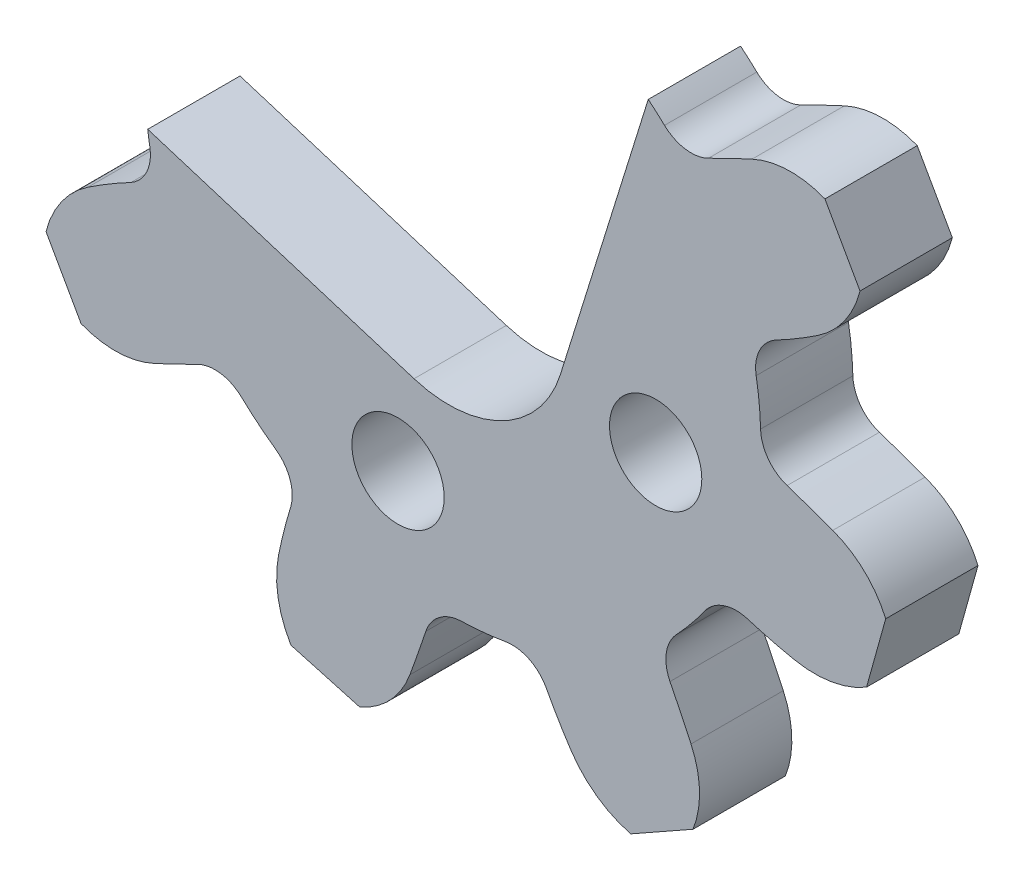
SolidWorks part; units mm, degrees
ref_plane "Front Plane" through (0, 0, 0) normal (0, 0, 1) x (1, 0, 0)
ref_plane "Top Plane" through (0, 0, 0) normal (0, 1, 0) x (1, 0, 0)
ref_plane "Right Plane" through (0, 0, 0) normal (1, 0, 0) x (0, 0, -1)
sketch "Sketch2" plane through (0, 0, 0) normal (0, 0, 1) x (1, 0, 0)
  line L0 (-5.1308, -13.1284) -> (-2.8946, -13.7516)
  line L5 (5.9154, -12.9172) -> (7.9373, -11.7766)
  line L6 (13.577, -4.957) -> (14.2002, -2.7208)
  line L7 (13.3658, 6.0892) -> (12.2252, 8.1111)
  line L8 (0.1374, 0.3112) -> (-9.7848, 0.3112) construction
  line L9 (0.1374, 0.3112) -> (0.1374, 8.1111) construction
  line L19 (6.4827, 8.0402) -> (3.6283, -1.1294)
  line L20 (-1.1294, -3.6283) -> (-9.7848, -0.9339)
  line L21 (-13.0911, -5.4669) -> (-11.9505, -7.4888)
  arc A0 (-5.1322, -9.223) -> (-5.5313, -10.7891) centre (10.0419, -13.9237) ccw
  arc A1 (-5.5313, -10.7891) -> (-5.1308, -13.1284) centre (-2.299, -11.4397) ccw
  arc A2 (-2.8946, -13.7516) -> (-1.2658, -12.0309) centre (-4.0784, -10.9998) ccw
  arc A3 (-1.2658, -12.0309) -> (-0.7472, -10.5464) centre (-49.4495, 5.6342) ccw
  arc A4 (0.4126, -9.685) -> (-0.7472, -10.5464) centre (0.4472, -10.9432) ccw
  arc A5 (-5.1322, -9.223) -> (-5.6219, -7.8638) centre (-6.3468, -8.8928) ccw
  arc A6 (3.1529, -10.1566) -> (3.9781, -11.5463) centre (17.2065, -2.7508) ccw
  arc A7 (3.9781, -11.5463) -> (5.9154, -12.9172) centre (6.7237, -9.7207) ccw
  arc A8 (7.9373, -11.7766) -> (7.8724, -9.4082) centre (5.1544, -10.6679) ccw
  arc A9 (7.8724, -9.4082) -> (7.1893, -7.9918) centre (-38.6897, -30.9881) ccw
  arc A10 (7.4004, -6.5626) -> (7.1893, -7.9918) centre (8.3145, -7.4278) ccw
  arc A11 (3.1529, -10.1566) -> (1.8456, -9.5418) centre (2.0606, -10.782) ccw
  arc A12 (9.6715, -4.9584) -> (11.2376, -5.3575) centre (14.3723, 10.2157) ccw
  arc A13 (11.2376, -5.3575) -> (13.577, -4.957) centre (11.8882, -2.1252) ccw
  arc A14 (14.2002, -2.7208) -> (12.4795, -1.092) centre (11.4483, -3.9046) ccw
  arc A15 (12.4795, -1.092) -> (10.9949, -0.5734) centre (-5.1856, -49.2757) ccw
  arc A16 (10.1336, 0.5864) -> (10.9949, -0.5734) centre (11.3917, 0.621) ccw
  arc A17 (9.6715, -4.9584) -> (8.3124, -5.4481) centre (9.3413, -6.173) ccw
  arc A18 (10.6052, 3.3267) -> (11.9948, 4.1519) centre (3.1994, 17.3804) ccw
  arc A19 (11.9948, 4.1519) -> (13.3658, 6.0892) centre (10.1693, 6.8975) ccw
  arc A20 (12.2252, 8.1111) -> (9.8568, 8.0462) centre (11.1165, 5.3282) ccw
  arc A21 (9.8568, 8.0462) -> (8.4403, 7.3631) centre (31.4367, -38.5159) ccw
  arc A22 (7.0112, 7.5742) -> (8.4403, 7.3631) centre (7.8763, 8.4883) ccw
  arc A23 (10.6052, 3.3267) -> (9.9904, 2.0194) centre (11.2305, 2.2344) ccw
  arc A25 (7.0112, 7.5742) -> (6.4827, 8.0402) centre (0.1374, 0.3112) ccw
  arc A26 (10.1336, 0.5864) -> (9.9904, 2.0194) centre (0.1374, 0.3112) ccw
  arc A27 (7.4004, -6.5626) -> (8.3124, -5.4481) centre (0.1374, 0.3112) ccw
  arc A28 (0.4126, -9.685) -> (1.8456, -9.5418) centre (0.1374, 0.3112) ccw
  arc A29 (-6.7364, -6.9518) -> (-5.6219, -7.8638) centre (0.1374, 0.3112) ccw
  circle A32 centre (-1.6501, -6.4856) radius 1.5
  circle A34 centre (6.7237, -1.7764) radius 1.5
  arc A83 (-1.1294, -3.6283) -> (3.6283, -1.1294) centre (0, 0) ccw
  arc A84 (-9.7848, -0.9339) -> (-9.7156, -1.397) centre (0.1374, 0.3112) ccw
  arc A85 (-10.3305, -2.7043) -> (-9.7156, -1.397) centre (-10.9558, -1.612) ccw
  arc A86 (-10.3305, -2.7043) -> (-11.7201, -3.5295) centre (-2.9246, -16.758) ccw
  arc A87 (-11.7201, -3.5295) -> (-13.0911, -5.4669) centre (-9.8945, -6.2751) ccw
  arc A88 (-11.9505, -7.4888) -> (-9.582, -7.4238) centre (-10.8417, -4.7058) ccw
  arc A89 (-9.582, -7.4238) -> (-8.1656, -6.7408) centre (-31.1619, 39.1383) ccw
  arc A90 (-6.7364, -6.9518) -> (-8.1656, -6.7408) centre (-7.6016, -7.866) ccw
  point P4 (-1.8775, 0.3112)
  point P139 (0.1374, 0.3112)
  dimension "D2" = 5
  dimension "D3" = 9.6036
  dimension "D4" = 3.8
  dimension "D5" = 1.2586
  dimension "D6" = 15.8856
  dimension "D7" = 3.2971
  dimension "D9" = 2.9957
  dimension "D10" = 51.3198
  dimension "D11" = 1.2586
  dimension "D12" = 3
  dimension "D13" = 3
  dimension "D1" = 9.065
  dimension "D8" = 2.3214
  dimension "D14" = 6.7968
  dimension "D15" = 17.291
  dimension "D16" = 17.291
  dimension "D17" = 6.5863
  dimension "D18" = 2.0876
  dimension "D19" = 1.7875
extrude "Boss-Extrude1" add sketch "Sketch2" along normal blind 3
